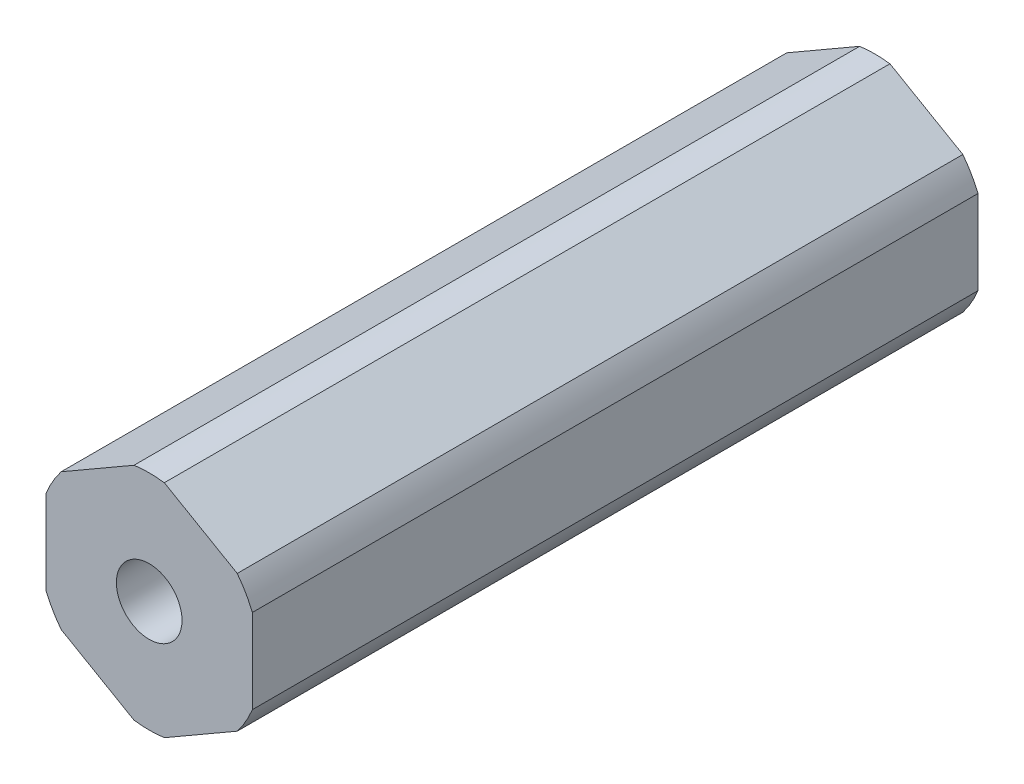
SolidWorks part; units mm, degrees
ref_plane "Front Plane" through (0, 0, 0) normal (0, 0, 1) x (1, 0, 0)
ref_plane "Top Plane" through (0, 0, 0) normal (0, 1, 0) x (1, 0, 0)
ref_plane "Right Plane" through (0, 0, 0) normal (1, 0, 0) x (0, 0, -1)
sketch "Sketch1" plane through (0, 0, 0) normal (0, 0, 1) x (1, 0, 0)
  line L1 (0, 7.3323) -> (-6.35, 3.6662)
  line L2 (-6.35, 3.6662) -> (-6.35, -3.6662)
  line L3 (-6.35, -3.6662) -> (0, -7.3323)
  line L4 (0, -7.3323) -> (6.35, -3.6662)
  line L5 (6.35, -3.6662) -> (6.35, 3.6662)
  line L6 (6.35, 3.6662) -> (0, 7.3323)
  circle A0 centre (0, 0) radius 6.35 construction
  circle A1 centre (0, 0) radius 6.858
  dimension "D1" = 12.7
  dimension "D2" = 13.716
extrude "Boss-Extrude1" add sketch "Sketch1" along normal mid plane 44.6532 contours L5 A1 L6 L1 L2 L3 L4
sketch "Sketch2" plane through (0, 0, 22.3266) normal (0, 0, 1) x (1, 0, 0)
  circle A0 centre (0, 0) radius 2.0193
  dimension "D1" = 4.0386
extrude "Cut-Extrude1" cut sketch "Sketch2" against normal through all
